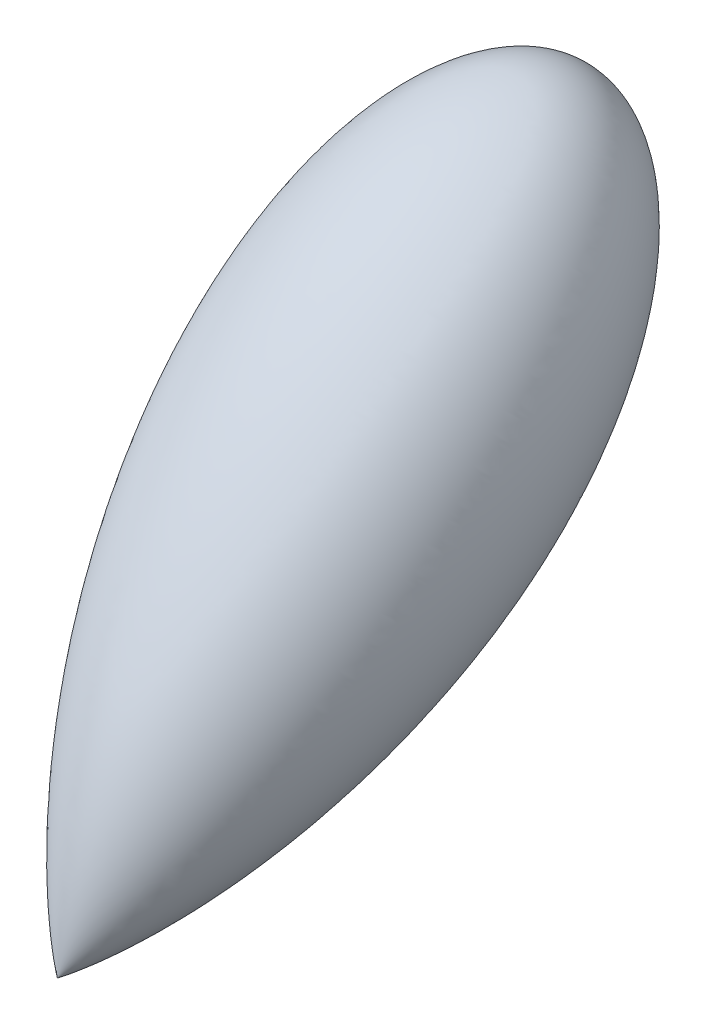
SolidWorks part; units mm, degrees
ref_plane "Front Plane" through (0, 0, 0) normal (0, 0, 1) x (1, 0, 0)
ref_plane "Top Plane" through (0, 0, 0) normal (0, 1, 0) x (1, 0, 0)
ref_plane "Right Plane" through (0, 0, 0) normal (1, 0, 0) x (0, 0, -1)
sketch "Sketch1" plane through (0, 0, 0) normal (1, 0, 0) x (0, 0, -1)
  line L0 (105.5058, 105.5058) -> (0, 0) construction
  line L1 (0, 0) -> (105.5058, 105.5058)
  spline S0 degree 4 poles (0, 0) (0.0944, 0.0011) (0.283, 0.005) (0.6602, 0.02) (1.2254, 0.0532) (1.8839, 0.1036) (2.8234, 0.1914) (3.9486, 0.3183) (5.5621, 0.533) (7.6586, 0.868) (10.7191, 1.4423) (14.7232, 2.3477) (19.3493, 3.5886) (25.8772, 5.6379) (33.5757, 8.4978) (42.3473, 12.3581) (52.0549, 17.4288) (61.4091, 23.1249) (70.3645, 29.4303) (78.8621, 36.3419) (86.823, 43.8679) (94.1376, 52.0276) (99.811, 59.7196) (103.6554, 66.1405) (106.044, 70.9891) (107.3666, 74.0676) (108.3265, 76.5931) (109.1717, 79.178) (109.8846, 81.8211) (110.4368, 84.4801) (110.8114, 87.1481) (110.9749, 89.6092) (110.9582, 91.8472) (110.7943, 93.8722) (110.5201, 95.6771) (110.13, 97.361) (109.693, 98.7448) (109.2665, 99.8383) (108.8333, 100.8046) (108.3589, 101.7343) (107.8315, 102.6237) (107.2492, 103.4716) (106.7303, 104.1476) (106.3421, 104.6113) (106.0078, 104.9856) (105.7412, 105.2667) (105.5396, 105.4731) (105.3569, 105.6539) (105.1225, 105.8795) (104.8728, 106.1083) (104.5419, 106.4) (104.1386, 106.7354) (103.6532, 107.1116) (103.082, 107.5174) (102.4942, 107.9) (101.8918, 108.2585) (101.268, 108.5973) (100.6236, 108.9152) (99.7913, 109.2866) (98.6612, 109.7231) (97.2254, 110.1684) (95.9381, 110.4565) (95.0014, 110.6147) (94.5313, 110.6819) knots 0 0 0 0 0 0.00208 0.00416 0.008321 0.012481 0.016642 0.024963 0.033284 0.048364 0.063444 0.093605 0.123766 0.153926 0.214248 0.274569 0.334891 0.395212 0.455533 0.515855 0.576176 0.636498 0.696819 0.726205 0.740898 0.755591 0.770671 0.785751 0.800832 0.815912 0.830507 0.845103 0.855156 0.86521 0.875264 0.885317 0.893221 0.897173 0.901125 0.908665 0.916205 0.919975 0.923745 0.927515 0.9294 0.931285 0.931932 0.933863 0.935795 0.937727 0.939658 0.943521 0.947385 0.951248 0.955111 0.958974 0.962838 0.966894 0.97095 0.979062 0.989531 1 1 1 1 1 construction
  spline S1 degree 4 poles (0, 0) (0.0944, 0.0011) (0.283, 0.005) (0.6602, 0.02) (1.2254, 0.0532) (1.8839, 0.1036) (2.8234, 0.1914) (3.9486, 0.3183) (5.5621, 0.533) (7.6586, 0.868) (10.7191, 1.4423) (14.7232, 2.3477) (19.3493, 3.5886) (25.8772, 5.6379) (33.5757, 8.4978) (42.3473, 12.3581) (52.0549, 17.4288) (61.4091, 23.1249) (70.3645, 29.4303) (78.8621, 36.3419) (86.823, 43.8679) (94.1376, 52.0276) (99.811, 59.7196) (103.6554, 66.1405) (106.044, 70.9891) (107.3666, 74.0676) (108.3265, 76.5931) (109.1717, 79.178) (109.8846, 81.8211) (110.4368, 84.4801) (110.8114, 87.1481) (110.9749, 89.6092) (110.9582, 91.8472) (110.7943, 93.8722) (110.5201, 95.6771) (110.13, 97.361) (109.693, 98.7448) (109.2665, 99.8383) (108.8333, 100.8046) (108.3589, 101.7343) (107.8315, 102.6237) (107.2492, 103.4716) (106.7303, 104.1476) (106.3421, 104.6113) (106.0078, 104.9856) (105.7412, 105.2667) (105.601, 105.4103) (105.5251, 105.4865) (105.5058, 105.5058) knots 0 0 0 0 0 0.00208 0.00416 0.008321 0.012481 0.016642 0.024963 0.033284 0.048364 0.063444 0.093605 0.123766 0.153926 0.214248 0.274569 0.334891 0.395212 0.455533 0.515855 0.576176 0.636498 0.696819 0.726205 0.740898 0.755591 0.770671 0.785751 0.800832 0.815912 0.830507 0.845103 0.855156 0.86521 0.875264 0.885317 0.893221 0.897173 0.901125 0.908665 0.916205 0.919975 0.923745 0.927515 0.9294 0.931285 0.931932 0.931932 0.931932 0.931932 0.931932
revolve "Revolve1" add sketch "Sketch1" angle 360 about L0
